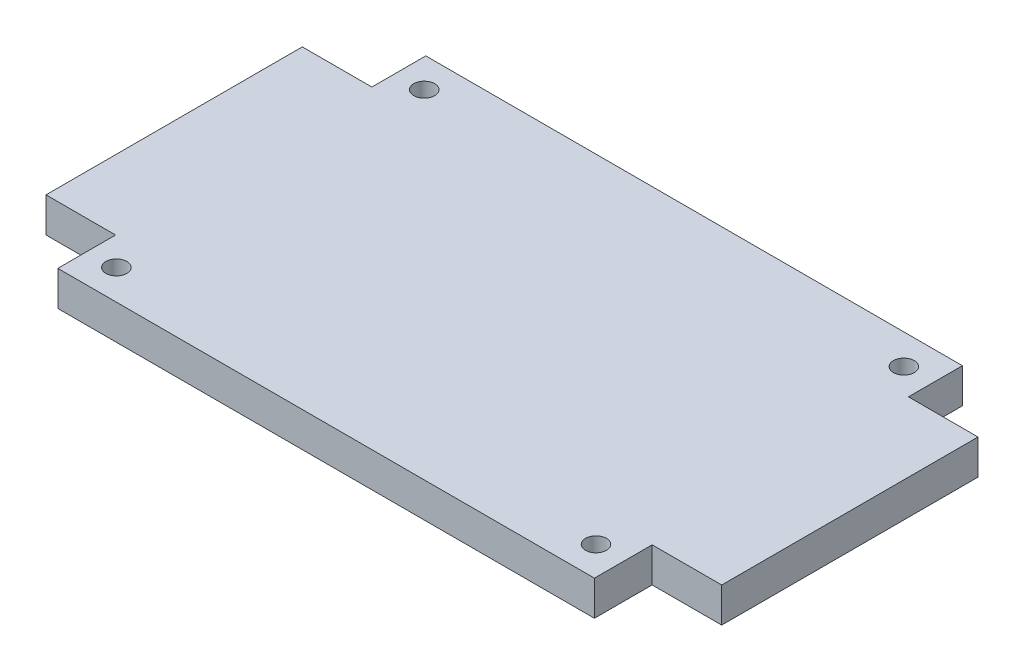
SolidWorks part; units mm, degrees
ref_plane "前视基准面" through (0, 0, 0) normal (0, 0, 1) x (1, 0, 0)
ref_plane "上视基准面" through (0, 0, 0) normal (0, 1, 0) x (1, 0, 0)
ref_plane "右视基准面" through (0, 0, 0) normal (1, 0, 0) x (0, 0, -1)
other "Configuration Table"
sketch "草图1" plane through (0, 0, 0) normal (0, 1, 0) x (1, 0, 0)
  line L0 (0, 0) -> (0, -47.806) construction
  line L1 (38.57, -26.45) -> (-38.57, -26.45)
  line L2 (38.57, -26.45) -> (38.57, 26.45)
  line L3 (38.57, 26.45) -> (-38.57, 26.45)
  line L4 (-38.57, -26.45) -> (-38.57, 26.45)
  line L5 (38.57, -26.45) -> (-38.57, 26.45) construction
  line L6 (38.57, 26.45) -> (-38.57, -26.45) construction
  line L7 (0, 0) -> (50000, 0) construction
  circle A0 centre (34.475, -22.13) radius 1.5
  circle A1 centre (34.475, 22.13) radius 1.5
  circle A2 centre (-34.475, 22.13) radius 1.5
  circle A3 centre (-34.475, -22.13) radius 1.5
  point P0 (0, 0)
  dimension "D5" = 3
  dimension "D1" = 77.14
  dimension "D2" = 52.9
  dimension "D3" = 68.95
  dimension "D4" = 44.26
extrude "凸台-拉伸1" add sketch "草图1" along normal blind 5
sketch "草图2" plane through (-38.57, 0, 0) normal (-1, 0, 0) x (0, 0, 1)
  line L0 (-26.45, 5) -> (26.45, 5) construction
  line L1 (-18.6947, 5) -> (18.1502, 5)
  line L2 (-18.6947, 5) -> (-18.6947, 0)
  line L3 (-18.6947, 0) -> (18.1502, 0)
  line L4 (18.1502, 5) -> (18.1502, 0)
  line L5 (-26.45, 0) -> (26.45, 0) construction
extrude "凸台-拉伸2" add sketch "草图2" along normal blind 10
mirror "镜向1" about plane through (0, 0, 0) normal (1, 0, 0) of "凸台-拉伸2"
